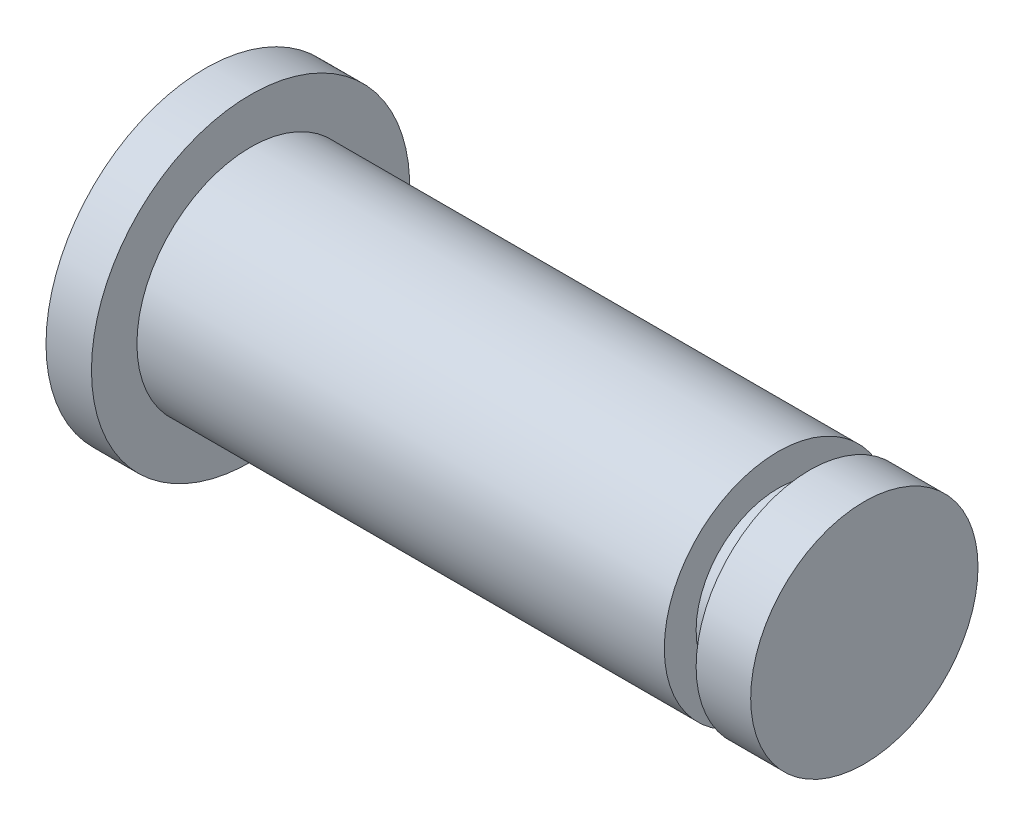
SolidWorks part; units mm, degrees
ref_plane "前视" through (0, 0, 0) normal (0, 0, 1) x (1, 0, 0)
ref_plane "上视" through (0, 0, 0) normal (0, 1, 0) x (1, 0, 0)
ref_plane "右视" through (0, 0, 0) normal (1, 0, 0) x (0, 0, -1)
sketch "草图1" plane through (0, 0, 0) normal (0, 0, 1) x (1, 0, 0)
  line L0 (0, 0) -> (145, 0)
  line L1 (0, 0) -> (0, 35)
  line L2 (0, 35) -> (10, 35)
  line L3 (10, 35) -> (10, 25)
  line L4 (10, 25) -> (126, 25)
  line L5 (126, 25) -> (126, 18)
  line L6 (126, 18) -> (133, 18)
  line L7 (133, 18) -> (133, 25)
  line L8 (133, 25) -> (145, 25)
  line L9 (145, 25) -> (145, 0)
  dimension "D1" = 145
  dimension "D2" = 35
  dimension "D3" = 10
  dimension "D4" = 25
  dimension "D5" = 116
  dimension "D6" = 7
  dimension "D7" = 18
revolve "旋转1" add sketch "草图1" angle 360 about L0
